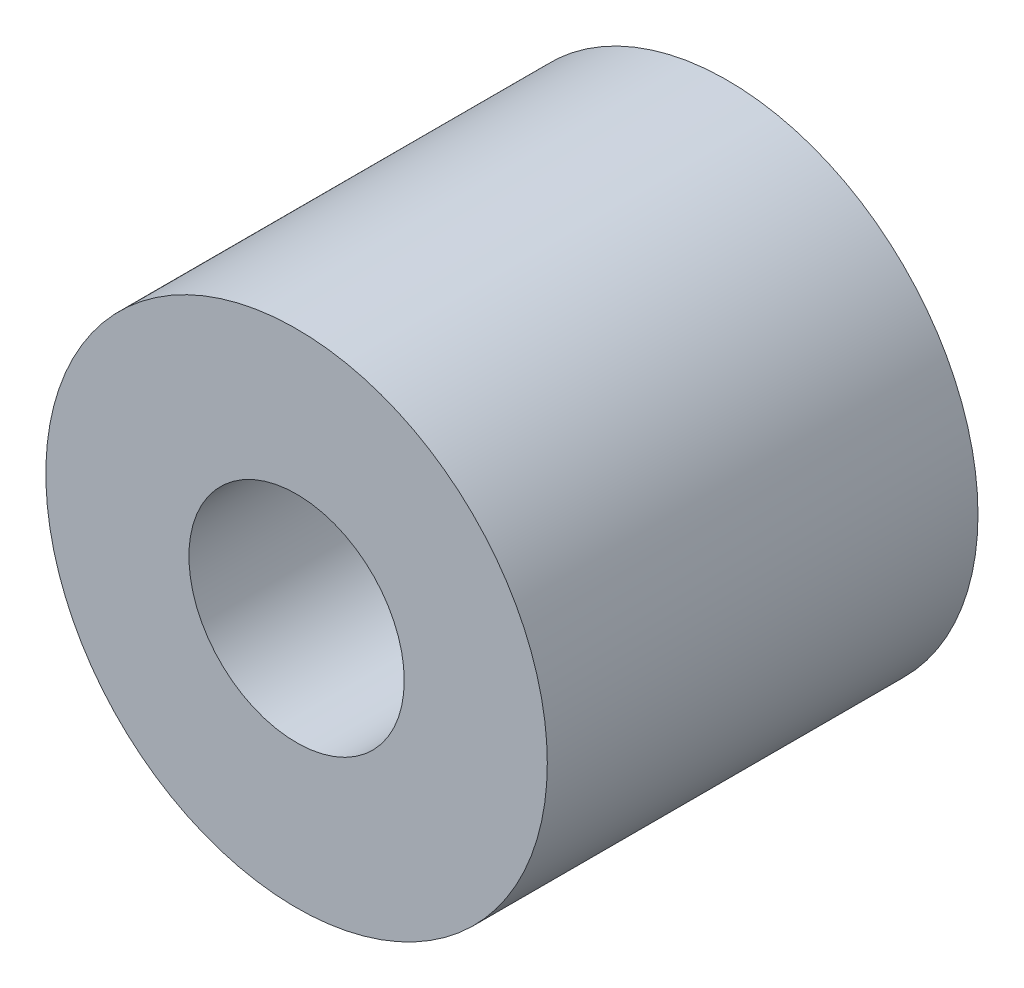
SolidWorks part; units mm, degrees
ref_plane "Front Plane" through (0, 0, 0) normal (1, 0, 0) x (0, 1, 0)
ref_plane "Top Plane" through (0, 0, 0) normal (0, 0, 1) x (0, 1, 0)
ref_plane "Right Plane" through (0, 0, 0) normal (0, 1, 0) x (-1, 0, 0)
sketch "Sketch1" plane through (0, 0, 0) normal (0, 0, 1) x (0, 1, 0)
  circle A0 centre (0, 0) radius 14.7875
  circle A1 centre (0, 0) radius 6.35
  dimension "D1" = 29.575
  dimension "D2" = 12.7
extrude "Boss-Extrude1" add sketch "Sketch1" against normal blind 25.4
